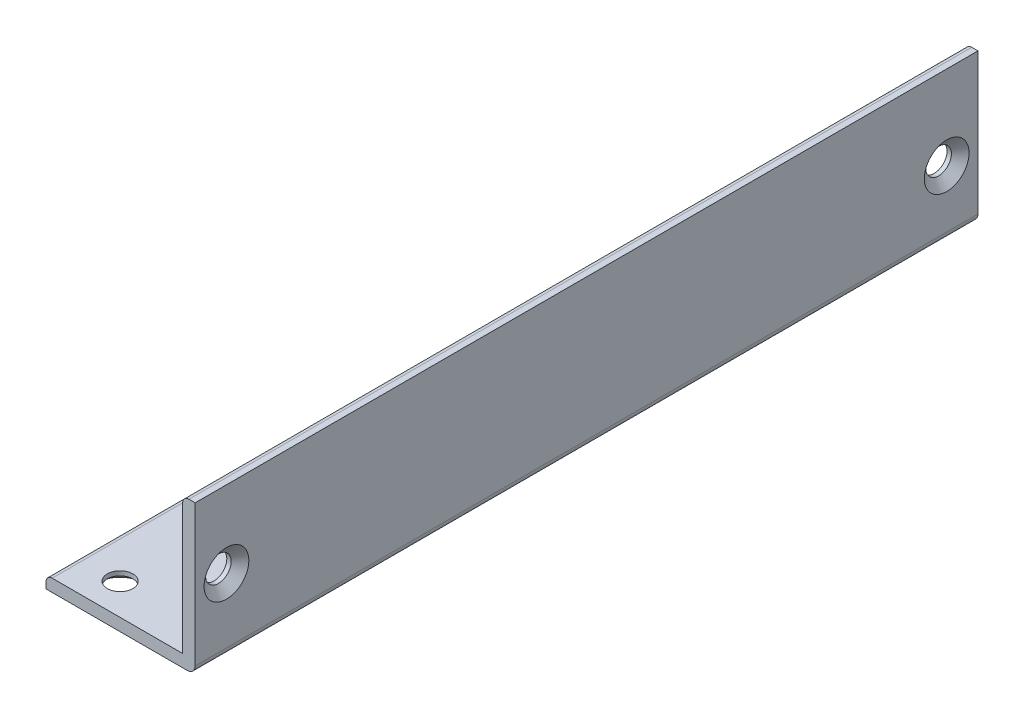
SolidWorks part; units mm, degrees
material "6061-T6 (SS)"
ref_plane "Front Plane" through (0, 0, 0) normal (0, 0, 1) x (1, 0, 0)
ref_plane "Top Plane" through (0, 0, 0) normal (0, 1, 0) x (1, 0, 0)
ref_plane "Right Plane" through (0, 0, 0) normal (1, 0, 0) x (0, 0, -1)
sketch "Sketch2" plane through (0, 0, 0) normal (0, 0, 1) x (1, 0, 0)
  line L0 (-9.525, 0) -> (9.525, 0)
  line L1 (9.525, 0) -> (9.525, 19.05)
  line L2 (9.525, 19.05) -> (7.9375, 19.05) construction
  line L3 (7.9375, 18.2563) -> (7.9375, 2.3812)
  line L4 (7.1438, 1.5875) -> (-8.7313, 1.5875)
  line L5 (-9.525, 0) -> (-9.525, 1.5875) construction
  line L6 (8.7313, 19.05) -> (9.525, 19.05)
  line L7 (-9.525, 0.7937) -> (-9.525, 0)
  arc A0 (7.9375, 18.2563) -> (8.7313, 19.05) centre (8.7313, 18.2563) cw
  arc A1 (-9.525, 0.7937) -> (-8.7313, 1.5875) centre (-8.7313, 0.7937) cw
  arc A2 (7.9375, 2.3812) -> (7.1438, 1.5875) centre (7.1438, 2.3812) cw
  dimension "Vert" = 19.05
  dimension "Horz" = 19.05
  dimension "Thickness" = 1.5875
extrude "Boss-Extrude1" add sketch "Sketch2" along normal mid plane 100
ref_plane "Contact Plane 1" through (0, 1.5875, 0) normal (0, 1, 0) x (1, 0, 0)
ref_plane "Contact Plane 2" through (7.9375, 0, 0) normal (-1, 0, 0) x (0, 0, 1)
sketch "Sketch6" plane through (0, 0, 0) normal (0, -1, 0) x (1, 0, 0)
  line L0 (9.525, 46) -> (-4.0625, 46) construction
  line L1 (9.525, 50) -> (9.525, -50) construction
  line L2 (-9.525, 50) -> (9.525, 50) construction
  line L3 (9.525, 0) -> (-9.525, 0) construction
  line L4 (-9.525, 50) -> (-9.525, -50) construction
  point P7 (-4.0625, 46)
  point P11 (-4.0625, -46)
  dimension "D1" = 4
  dimension "D2" = 13.5875
hole_wizard "CSK for #4 Flat Head Machine Screw (100)1" positions "Sketch7" profile "Sketch8" countersink size "#4" standard "ANSI Inch" end condition through all
sketch "Sketch7" plane through (0, 0, 0) normal (0, -1, 0) x (-1, 0, 0)
  point P0 (4.0625, -46)
  point P3 (4.0625, 46)
sketch "Sketch8" plane through (-4.0625, 0, 46) normal (1, 0, 0) x (0, 0, -1)
  line L0 (0, 0) -> (0, 19.05)
  line L1 (0, 19.05) -> (1.6319, 19.05)
  line L2 (1.6319, 19.05) -> (1.6319, 1.0284)
  line L3 (1.6319, 1.0284) -> (2.8575, 0)
  line L5 (2.8575, 0) -> (0, 0)
  line L6 (-1.6319, 1.0284) -> (-2.8575, 0) construction
  line L11 (0, -6.35) -> (0, 107.95) construction
  dimension "Thru Hole Dia." = 3.2639
  dimension "Thru Hole Depth" = 19.05
  dimension "Near C'Sink Dia." = 5.715
  dimension "Near C'Sink Angle" = 100
sketch "Sketch9" plane through (9.525, 0, 0) normal (1, 0, 0) x (0, 0, -1)
  line L0 (-46, 0) -> (-46, 9.25) construction
  line L4 (-50, 0) -> (50, 0) construction
  line L5 (50, 0) -> (50, 19.05) construction
  point P4 (-46, 9.25)
  point P10 (46, 8.34)
  dimension "D1" = 9.25
  dimension "D2" = 8.34
  dimension "D3" = 4
hole_wizard "CSK for #4 Flat Head Machine Screw (100)2" positions "Sketch10" profile "Sketch11" countersink size "#4" standard "ANSI Inch" end condition through all
sketch "Sketch10" plane through (9.525, 0, 0) normal (1, 0, 0) x (0, 0, -1)
  point P0 (-46, 9.25)
  point P3 (46, 8.34)
sketch "Sketch11" plane through (9.525, 9.25, 46) normal (0, 1, 0) x (0, 0, -1)
  line L0 (0, 0) -> (0, 19.05)
  line L1 (0, 19.05) -> (1.6319, 19.05)
  line L2 (1.6319, 19.05) -> (1.6319, 1.0284)
  line L3 (1.6319, 1.0284) -> (2.8575, 0)
  line L5 (2.8575, 0) -> (0, 0)
  line L6 (-1.6319, 1.0284) -> (-2.8575, 0) construction
  line L11 (0, -6.35) -> (0, 107.95) construction
  dimension "Thru Hole Dia." = 3.2639
  dimension "Thru Hole Depth" = 19.05
  dimension "Near C'Sink Dia." = 5.715
  dimension "Near C'Sink Angle" = 100
fillet "Fillet1" radius 1 1 edges at (9.525, 0, 0)
sketch "Sketch27" plane through (0, 1.5875, 0) normal (0, 1, 0) x (1, 0, 0)
  line L0 (7.1438, -50) -> (7.1438, 50) construction
  line L1 (7.1438, -50) -> (-8.7313, -50) construction
  point P0 (3.4938, -29.88)
  point P1 (-1.3062, -29.88)
  dimension "D1" = 4.8
  dimension "D2" = 3.65
  dimension "D3" = 20.12
hole_wizard "#2 Clearance Hole1" positions "Sketch28" profile "Sketch30" hole size "#2" standard "ANSI Inch" end condition through all
sketch "Sketch28" plane through (0, 1.5875, 0) normal (0, 1, 0) x (1, 0, 0)
  point P0 (3.4938, -29.88)
  point P3 (-1.3062, -29.88)
sketch "Sketch30" plane through (3.4938, 1.5875, 29.88) normal (1, 0, 0) x (0, 0, 1)
  line L0 (0, 0) -> (0, 1.5875)
  line L1 (0, 1.5875) -> (2.0574, 1.5875)
  line L2 (1.2192, 0.6233) -> (1.2192, 0)
  line L5 (1.2192, 0) -> (0, 0)
  line L7 (2.0574, 1.5875) -> (1.2192, 0.6233)
  line L8 (-2.0574, 1.5875) -> (-1.2192, 0.6233) construction
  line L11 (0, -6.35) -> (0, 107.95) construction
  dimension "Thru Hole Dia." = 2.4384
  dimension "Thru Hole Depth" = 1.5875
  dimension "Far C'Sink Dia." = 4.1148
  dimension "Far C'Sink Angle" = 82
sketch "Sketch15" [suppressed] plane through (9.525, 0, 0) normal (1, 0, 0) x (0, 0, -1)
  line L0 (-96, 13.5875) -> (96, 13.5875) construction
  point P4 (0, 13.5875)
sketch "Sketch16" [suppressed] plane through (0, 0, 0) normal (0, -1, 0) x (1, 0, 0)
  line L0 (-4.0625, 96) -> (-4.0625, -96) construction
  point P4 (-4.0625, 0)
hole_wizard "CSK for #4 Flat Head Machine Screw (100)3" [suppressed] positions "Sketch17" profile "Sketch18" countersink size "#4" standard "ANSI Inch"
sketch "Sketch17" plane through (0, 0, 0) normal (0, -1, 0) x (-1, 0, 0)
  point P0 (4.0625, 0)
sketch "Sketch18" plane through (-4.0625, 0, 0) normal (1, 0, 0) x (0, 0, -1)
  line L0 (0, 0) -> (0, 8.5806)
  line L1 (0, 8.5806) -> (1.6319, 7.6)
  line L2 (1.6319, 7.6) -> (1.6319, 1.0284)
  line L3 (1.6319, 1.0284) -> (2.8575, 0)
  line L5 (2.8575, 0) -> (0, 0)
  line L6 (-1.6319, 1.0284) -> (-2.8575, 0) construction
  line L10 (0, 8.5806) -> (-1.632, 7.6) construction
  line L11 (0, -6.35) -> (0, 107.95) construction
  dimension "Hole Dia." = 3.2639
  dimension "Hole Depth" = 7.6
  dimension "Near C'Sink Dia." = 5.715
  dimension "Near C'Sink Angle" = 100
  dimension "Drill Angle" = 118
hole_wizard "CSK for #4 Flat Head Machine Screw (100)4" [suppressed] positions "Sketch19" profile "Sketch20" countersink size "#4" standard "ANSI Inch"
sketch "Sketch19" plane through (9.525, 0, 0) normal (1, 0, 0) x (0, 0, -1)
  point P0 (0, 13.5875)
sketch "Sketch20" plane through (9.525, 13.5875, 0) normal (0, 1, 0) x (0, 0, -1)
  line L0 (0, 0) -> (0, 8.5806)
  line L1 (0, 8.5806) -> (1.6319, 7.6)
  line L2 (1.6319, 7.6) -> (1.6319, 1.0284)
  line L3 (1.6319, 1.0284) -> (2.8575, 0)
  line L5 (2.8575, 0) -> (0, 0)
  line L6 (-1.6319, 1.0284) -> (-2.8575, 0) construction
  line L10 (0, 8.5806) -> (-1.6319, 7.6) construction
  line L11 (0, -6.35) -> (0, 107.95) construction
  dimension "Hole Dia." = 3.2639
  dimension "Hole Depth" = 7.6
  dimension "Near C'Sink Dia." = 5.715
  dimension "Near C'Sink Angle" = 100
  dimension "Drill Angle" = 118
sketch "Sketch21" [suppressed] plane through (9.525, 0, 0) normal (1, 0, 0) x (0, 0, -1)
  line L0 (-146, 13.5875) -> (-150, 13.5875) construction
  line L1 (-150, 1) -> (-150, 19.05) construction
  line L2 (-150, 13.5875) -> (-50, 13.5875) construction
  line L3 (150, 13.5875) -> (50, 13.5875) construction
  line L4 (150, 1) -> (150, 19.05) construction
  point P11 (-50, 13.5875)
  point P12 (50, 13.5875)
  dimension "D1" = 100
  dimension "D2" = 100
hole_wizard "CSK for #4 Flat Head Machine Screw (100)5" [suppressed] positions "Sketch22" profile "Sketch23" countersink size "#4" standard "ANSI Inch"
sketch "Sketch22" plane through (9.525, 0, 0) normal (1, 0, 0) x (0, 0, -1)
  point P0 (-50, 13.5875)
  point P3 (50, 13.5875)
sketch "Sketch23" plane through (9.525, 13.5875, 50) normal (0, 1, 0) x (0, 0, -1)
  line L0 (0, 0) -> (0, 8.5806)
  line L1 (0, 8.5806) -> (1.6319, 7.6)
  line L2 (1.6319, 7.6) -> (1.6319, 1.0284)
  line L3 (1.6319, 1.0284) -> (2.8575, 0)
  line L5 (2.8575, 0) -> (0, 0)
  line L6 (-1.6319, 1.0284) -> (-2.8575, 0) construction
  line L10 (0, 8.5806) -> (-1.6319, 7.6) construction
  line L11 (0, -6.35) -> (0, 107.95) construction
  dimension "Hole Dia." = 3.2639
  dimension "Hole Depth" = 7.6
  dimension "Near C'Sink Dia." = 5.715
  dimension "Near C'Sink Angle" = 100
  dimension "Drill Angle" = 118
sketch "Sketch24" [suppressed] plane through (0, 0, 0) normal (0, -1, 0) x (1, 0, 0)
  line L0 (-4.0625, 146) -> (-4.0625, 150) construction
  line L1 (-9.525, 150) -> (8.525, 150) construction
  line L2 (-4.0625, 150) -> (-4.0625, 50) construction
  line L3 (-4.0625, -150) -> (-4.0625, -50) construction
  line L4 (-9.525, -150) -> (8.525, -150) construction
  point P11 (-4.0625, 50)
  point P12 (-4.0625, -50)
  dimension "D1" = 100
  dimension "D2" = 100
hole_wizard "CSK for #4 Flat Head Machine Screw (100)6" [suppressed] positions "Sketch25" profile "Sketch26" countersink size "#4" standard "ANSI Inch"
sketch "Sketch25" plane through (0, 0, 0) normal (0, -1, 0) x (-1, 0, 0)
  point P0 (4.0625, -50)
  point P3 (4.0625, 50)
sketch "Sketch26" plane through (-4.0625, 0, 50) normal (1, 0, 0) x (0, 0, -1)
  line L0 (0, 0) -> (0, 8.5806)
  line L1 (0, 8.5806) -> (1.6319, 7.6)
  line L2 (1.6319, 7.6) -> (1.6319, 1.0284)
  line L3 (1.6319, 1.0284) -> (2.8575, 0)
  line L5 (2.8575, 0) -> (0, 0)
  line L6 (-1.6319, 1.0284) -> (-2.8575, 0) construction
  line L10 (0, 8.5806) -> (-1.6319, 7.6) construction
  line L11 (0, -6.35) -> (0, 107.95) construction
  dimension "Hole Dia." = 3.2639
  dimension "Hole Depth" = 7.6
  dimension "Near C'Sink Dia." = 5.715
  dimension "Near C'Sink Angle" = 100
  dimension "Drill Angle" = 118
sketch "Sketch31" plane through (0, 0, 0) normal (0, -1, 0) x (1, 0, 0)
  line L0 (-4.0625, -46) -> (-4.0625, -50) construction
  line L1 (-9.525, -50) -> (8.525, -50) construction
  line L2 (-4.0625, -50) -> (-4.0625, 50) construction
  point P7 (-4.0625, 50)
  dimension "D1" = 100
hole_wizard "CSK for #4 Flat Head Machine Screw (100)7" [suppressed] positions "Sketch32" profile "Sketch33" countersink size "#4" standard "ANSI Inch"
sketch "Sketch32" plane through (0, 0, 0) normal (0, -1, 0) x (-1, 0, 0)
  point P0 (4.0625, 0)
sketch "Sketch33" plane through (-4.0625, 0, 0) normal (1, 0, 0) x (0, 0, -1)
  line L0 (0, 0) -> (0, 6.6706)
  line L1 (0, 6.6706) -> (1.6319, 5.69)
  line L2 (1.6319, 5.69) -> (1.6319, 1.0284)
  line L3 (1.6319, 1.0284) -> (2.8575, 0)
  line L5 (2.8575, 0) -> (0, 0)
  line L6 (-1.6319, 1.0284) -> (-2.8575, 0) construction
  line L10 (0, 6.6706) -> (-1.632, 5.69) construction
  line L11 (0, -6.35) -> (0, 107.95) construction
  dimension "Hole Dia." = 3.2639
  dimension "Hole Depth" = 5.69
  dimension "Near C'Sink Dia." = 5.715
  dimension "Near C'Sink Angle" = 100
  dimension "Drill Angle" = 118
sketch "Sketch34" plane through (9.525, 0, 0) normal (1, 0, 0) x (0, 0, -1)
  line L0 (46, 8.34) -> (50, 8.34) construction
  line L1 (50, 1) -> (50, 19.05) construction
  line L2 (50, 8.34) -> (-50, 8.34) construction
  point P7 (-50, 8.34)
  dimension "D1" = 100
hole_wizard "CSK for #4 Flat Head Machine Screw (100)8" [suppressed] positions "Sketch35" profile "Sketch36" countersink size "#4" standard "ANSI Inch"
sketch "Sketch35" plane through (9.525, 0, 0) normal (1, 0, 0) x (0, 0, -1)
  point P0 (0, 8.34)
sketch "Sketch36" plane through (9.525, 8.34, 0) normal (0, 1, 0) x (0, 0, -1)
  line L0 (0, 0) -> (0, 6.6706)
  line L1 (0, 6.6706) -> (1.6319, 5.69)
  line L2 (1.6319, 5.69) -> (1.6319, 1.0284)
  line L3 (1.6319, 1.0284) -> (2.8575, 0)
  line L5 (2.8575, 0) -> (0, 0)
  line L6 (-1.6319, 1.0284) -> (-2.8575, 0) construction
  line L10 (0, 6.6706) -> (-1.6319, 5.69) construction
  line L11 (0, -6.35) -> (0, 107.95) construction
  dimension "Hole Dia." = 3.2639
  dimension "Hole Depth" = 5.69
  dimension "Near C'Sink Dia." = 5.715
  dimension "Near C'Sink Angle" = 100
  dimension "Drill Angle" = 118
sketch "Sketch37" plane through (9.525, 0, 0) normal (1, 0, 0) x (0, 0, -1)
  line L0 (-50, 8.34) -> (-150, 8.34) construction
  point P4 (-150, 8.34)
  dimension "D1" = 100
hole_wizard "CSK for #4 Flat Head Machine Screw (100)9" [suppressed] positions "Sketch38" profile "Sketch39" countersink size "#4" standard "ANSI Inch"
sketch "Sketch38" plane through (9.525, 0, 0) normal (1, 0, 0) x (0, 0, -1)
  point P0 (-50, 8.34)
sketch "Sketch39" plane through (9.525, 8.34, 50) normal (0, 1, 0) x (0, 0, -1)
  line L0 (0, 0) -> (0, 6.6706)
  line L1 (0, 6.6706) -> (1.6319, 5.69)
  line L2 (1.6319, 5.69) -> (1.6319, 1.0284)
  line L3 (1.6319, 1.0284) -> (2.8575, 0)
  line L5 (2.8575, 0) -> (0, 0)
  line L6 (-1.6319, 1.0284) -> (-2.8575, 0) construction
  line L10 (0, 6.6706) -> (-1.6319, 5.69) construction
  line L11 (0, -6.35) -> (0, 107.95) construction
  dimension "Hole Dia." = 3.2639
  dimension "Hole Depth" = 5.69
  dimension "Near C'Sink Dia." = 5.715
  dimension "Near C'Sink Angle" = 100
  dimension "Drill Angle" = 118
sketch "Sketch40" plane through (0, 0, 0) normal (0, -1, 0) x (1, 0, 0)
  line L0 (-4.0625, 50) -> (-4.0625, 150) construction
  point P4 (-4.0625, 150)
  dimension "D1" = 100
hole_wizard "CSK for #4 Flat Head Machine Screw (100)10" [suppressed] positions "Sketch41" profile "Sketch42" countersink size "#4" standard "ANSI Inch"
sketch "Sketch41" plane through (0, 0, 0) normal (0, -1, 0) x (-1, 0, 0)
  point P0 (4.0625, -50)
sketch "Sketch42" plane through (-4.0625, 0, 50) normal (1, 0, 0) x (0, 0, -1)
  line L0 (0, 0) -> (0, 6.6706)
  line L1 (0, 6.6706) -> (1.6319, 5.69)
  line L2 (1.6319, 5.69) -> (1.6319, 1.0284)
  line L3 (1.6319, 1.0284) -> (2.8575, 0)
  line L5 (2.8575, 0) -> (0, 0)
  line L6 (-1.6319, 1.0284) -> (-2.8575, 0) construction
  line L10 (0, 6.6706) -> (-1.6319, 5.69) construction
  line L11 (0, -6.35) -> (0, 107.95) construction
  dimension "Hole Dia." = 3.2639
  dimension "Hole Depth" = 5.69
  dimension "Near C'Sink Dia." = 5.715
  dimension "Near C'Sink Angle" = 100
  dimension "Drill Angle" = 118
sketch "Sketch43" plane through (0, 0, -50) normal (0, 0, -1) x (-1, 0, 0)
  line L0 (-7.9375, 6.5875) -> (-7.9375, 1.5875)
  line L1 (-7.9375, 18.2563) -> (-7.9375, 2.3812) construction
  line L3 (-7.1438, 1.5875) -> (8.7313, 1.5875) construction
  line L4 (-2.9375, 1.5875) -> (-7.9375, 1.5875)
  line L6 (-7.9375, 6.5875) -> (-2.9375, 1.5875)
  dimension "D1" = 5
  dimension "D2" = 5
extrude "Cut-Extrude1" cut sketch "Sketch43" against normal blind 25
ref_plane "Plane1" through (0, 0, 0) normal (0, 0, -1) x (-1, 0, 0)
mirror "Mirror1" about plane through (0, 0, 0) normal (0, 0, -1) of "Cut-Extrude1"
